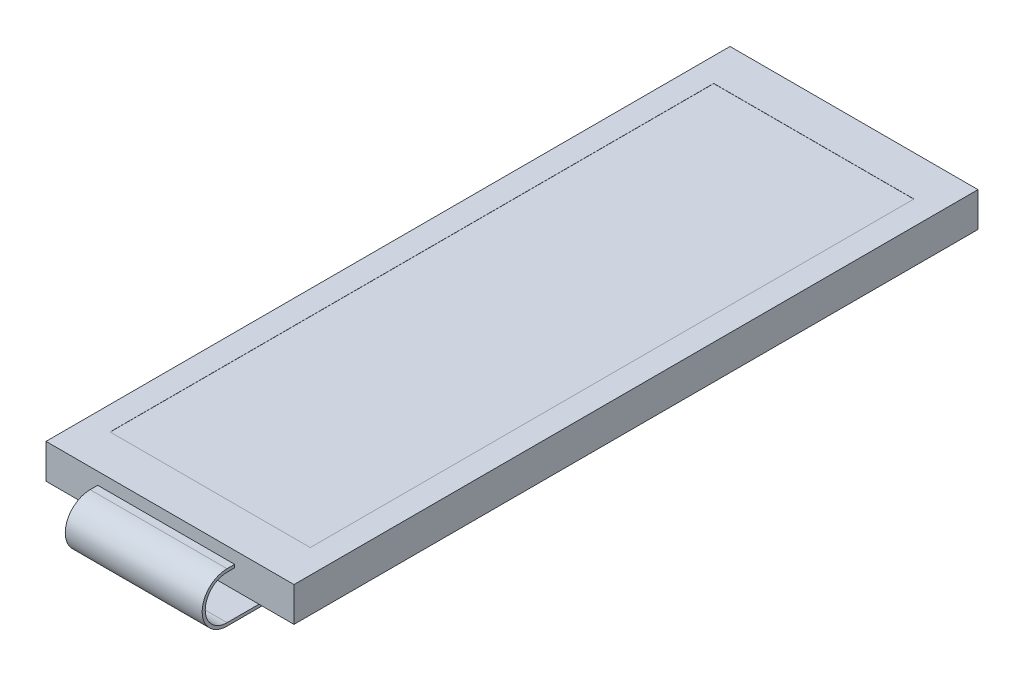
SolidWorks part; units mm, degrees
ref_plane "前视基准面" through (0, 0, 0) normal (0, 0, 1) x (1, 0, 0)
ref_plane "上视基准面" through (0, 0, 0) normal (0, 1, 0) x (1, 0, 0)
ref_plane "右视基准面" through (0, 0, 0) normal (1, 0, 0) x (0, 0, -1)
other "Configuration Table"
sketch "草图1" plane through (0, 0, 0) normal (0, 1, 0) x (1, 0, 0)
  line L1 (-8.15, 22.48) -> (8.15, 22.48)
  line L2 (-8.15, 22.48) -> (-8.15, -22.48)
  line L3 (-8.15, -22.48) -> (8.15, -22.48)
  line L4 (8.15, 22.48) -> (8.15, -22.48)
  line L5 (-8.15, 22.48) -> (8.15, -22.48) construction
  line L6 (-8.15, -22.48) -> (8.15, 22.48) construction
  point P0 (0, 0)
  dimension "D1" = 44.96
  dimension "D2" = 16.3
extrude "凸台-拉伸1" add sketch "草图1" along normal blind 2.27
sketch "草图2" plane through (0, 2.27, 0) normal (0, 1, 0) x (1, 0, 0)
  line L1 (-6.58, -19.84) -> (6.58, -19.84)
  line L2 (-6.58, -19.84) -> (-6.58, 19.84)
  line L3 (-6.58, 19.84) -> (6.58, 19.84)
  line L4 (6.58, -19.84) -> (6.58, 19.84)
  line L5 (-6.58, -19.84) -> (6.58, 19.84) construction
  line L6 (-6.58, 19.84) -> (6.58, -19.84) construction
  point P0 (0, 0)
  point P6 (0, 0)
  dimension "D1" = 39.68
  dimension "D2" = 13.16
extrude "切除-拉伸1" cut sketch "草图2" against normal blind 0.01
ref_plane "基准面1" through (0, 1.27, 0) normal (0, 1, 0) x (1, 0, 0)
sketch "草图3" plane through (0, 1.27, 0) normal (0, 1, 0) x (1, 0, 0)
  line L0 (-8.15, -22.48) -> (8.15, -22.48) construction
  line L1 (-4.75, -22.48) -> (4.25, -22.48)
  line L2 (-4.75, -22.48) -> (-4.75, -22.98)
  line L3 (-4.75, -22.98) -> (4.25, -22.98)
  line L4 (4.25, -22.48) -> (4.25, -22.98)
  line L5 (8.15, -22.48) -> (8.15, 22.48) construction
  dimension "D1" = 9
  dimension "D2" = 3.9
  dimension "D3" = 0.5
extrude "凸台-拉伸2" add sketch "草图3" along normal blind 0.2
sketch "草图4" plane through (4.25, 0, 0) normal (1, 0, 0) x (0, 0, -1)
  line L0 (-22.73, 1.47) -> (-22.98, 1.47)
  line L1 (-22.98, 1.47) -> (-22.48, 1.47) construction
  line L2 (-22.98, -1.8) -> (-10.48, -1.8)
  line L3 (-10.48, -1.8) -> (-10.48, -1.6)
  line L4 (-10.48, -1.6) -> (-22.98, -1.6)
  line L5 (8.965, 1.27) -> (-8.965, 1.27) construction
  line L6 (-22.98, 1.27) -> (-22.73, 1.27)
  line L7 (-22.73, 1.27) -> (-22.73, 1.47)
  line L8 (-22.48, 2.27) -> (-22.48, 0) construction
  line L9 (-22.48, 0) -> (22.48, 0) construction
  arc A0 (-22.98, 1.47) -> (-22.98, -1.8) centre (-22.98, -0.165) ccw
  arc A1 (-22.98, -1.6) -> (-22.98, 1.27) centre (-22.98, -0.165) cw
  dimension "D1" = 12
  dimension "D2" = 1.6
extrude "凸台-拉伸3" add sketch "草图4" against normal up to surface (9 mm away) up to face at (-4.75, 1.37, 22.73)
sketch "草图5" plane through (0, -1.8, 0) normal (0, -1, 0) x (1, 0, 0)
  line L0 (-0.25, 26.1191) -> (-0.25, 14.9215) construction
  line L1 (-4.75, 10.48) -> (-4.75, 22.98) construction
  line L2 (4.25, 22.98) -> (4.25, 10.48) construction
  line L3 (-4.75, 10.48) -> (4.25, 10.48) construction
  line L4 (-6.45, 15.58) -> (5.95, 15.58)
  line L5 (-6.45, 15.58) -> (-6.45, 10.48)
  line L6 (-6.45, 10.48) -> (5.95, 10.48)
  line L7 (5.95, 15.58) -> (5.95, 10.48)
  line L8 (-6.45, 15.58) -> (5.95, 10.48) construction
  line L9 (-6.45, 10.48) -> (5.95, 15.58) construction
  point P6 (-0.25, 13.03)
  dimension "D1" = 5.1
  dimension "D2" = 12.4
extrude "凸台-拉伸4" add sketch "草图5" against normal up to surface (0.2 mm away) up to face at (-0.25, -1.6, 16.73)
sketch "草图6" plane through (0, -1.8, 0) normal (0, -1, 0) x (1, 0, 0)
  line L0 (-6.45, 10.48) -> (5.95, 10.48) construction
  line L1 (-4.625, 12.48) -> (-4.275, 12.48)
  line L2 (-4.625, 12.48) -> (-4.625, 10.48)
  line L3 (-4.625, 10.48) -> (-4.275, 10.48)
  line L4 (-4.275, 12.48) -> (-4.275, 10.48)
  line L5 (-3.925, 12.48) -> (-3.925, 10.48)
  line L6 (-3.925, 12.48) -> (-3.575, 12.48)
  line L7 (-3.575, 12.48) -> (-3.575, 10.48)
  line L8 (-3.925, 10.48) -> (-3.575, 10.48)
  line L9 (-3.225, 12.48) -> (-3.225, 10.48)
  line L10 (-3.225, 12.48) -> (-2.875, 12.48)
  line L11 (-2.875, 12.48) -> (-2.875, 10.48)
  line L12 (-3.225, 10.48) -> (-2.875, 10.48)
  line L13 (-2.525, 12.48) -> (-2.525, 10.48)
  line L14 (-2.525, 12.48) -> (-2.175, 12.48)
  line L15 (-2.175, 12.48) -> (-2.175, 10.48)
  line L16 (-2.525, 10.48) -> (-2.175, 10.48)
  line L17 (-1.825, 12.48) -> (-1.825, 10.48)
  line L18 (-1.825, 12.48) -> (-1.475, 12.48)
  line L19 (-1.475, 12.48) -> (-1.475, 10.48)
  line L20 (-1.825, 10.48) -> (-1.475, 10.48)
  line L21 (-1.125, 12.48) -> (-1.125, 10.48)
  line L22 (-1.125, 12.48) -> (-0.775, 12.48)
  line L23 (-0.775, 12.48) -> (-0.775, 10.48)
  line L24 (-1.125, 10.48) -> (-0.775, 10.48)
  line L25 (-0.425, 12.48) -> (-0.425, 10.48)
  line L26 (-0.425, 12.48) -> (-0.075, 12.48)
  line L27 (-0.075, 12.48) -> (-0.075, 10.48)
  line L28 (-0.425, 10.48) -> (-0.075, 10.48)
  line L29 (0.275, 12.48) -> (0.275, 10.48)
  line L30 (0.275, 12.48) -> (0.625, 12.48)
  line L31 (0.625, 12.48) -> (0.625, 10.48)
  line L32 (0.275, 10.48) -> (0.625, 10.48)
  line L33 (0.975, 12.48) -> (0.975, 10.48)
  line L34 (0.975, 12.48) -> (1.325, 12.48)
  line L35 (1.325, 12.48) -> (1.325, 10.48)
  line L36 (0.975, 10.48) -> (1.325, 10.48)
  line L37 (1.675, 12.48) -> (1.675, 10.48)
  line L38 (1.675, 12.48) -> (2.025, 12.48)
  line L39 (2.025, 12.48) -> (2.025, 10.48)
  line L40 (1.675, 10.48) -> (2.025, 10.48)
  line L41 (2.375, 12.48) -> (2.375, 10.48)
  line L42 (2.375, 12.48) -> (2.725, 12.48)
  line L43 (2.725, 12.48) -> (2.725, 10.48)
  line L44 (2.375, 10.48) -> (2.725, 10.48)
  line L45 (3.075, 12.48) -> (3.075, 10.48)
  line L46 (3.075, 12.48) -> (3.425, 12.48)
  line L47 (3.425, 12.48) -> (3.425, 10.48)
  line L48 (3.075, 10.48) -> (3.425, 10.48)
  line L49 (3.775, 12.48) -> (3.775, 10.48)
  line L50 (3.775, 12.48) -> (4.125, 12.48)
  line L51 (4.125, 12.48) -> (4.125, 10.48)
  line L52 (3.775, 10.48) -> (4.125, 10.48)
  line L53 (-0.25, 20.6209) -> (-0.25, 6.2444) construction
  line L54 (4.25, 22.98) -> (4.25, 15.58) construction
  line L55 (-4.75, 15.58) -> (-4.75, 22.98) construction
  dimension "D1" = 0.35
  dimension "D2" = 2
  dimension "D3" = 13
extrude "切除-拉伸2" cut sketch "草图6" against normal blind 0.05
fillet "圆角2" radius 0.5 6 edges at (-4.75, -1.7, 15.58) (5.95, -1.7, 10.48) (5.95, -1.7, 15.58) (4.25, -1.7, 15.58) (-6.45, -1.7, 10.48) (-6.45, -1.7, 15.58)
